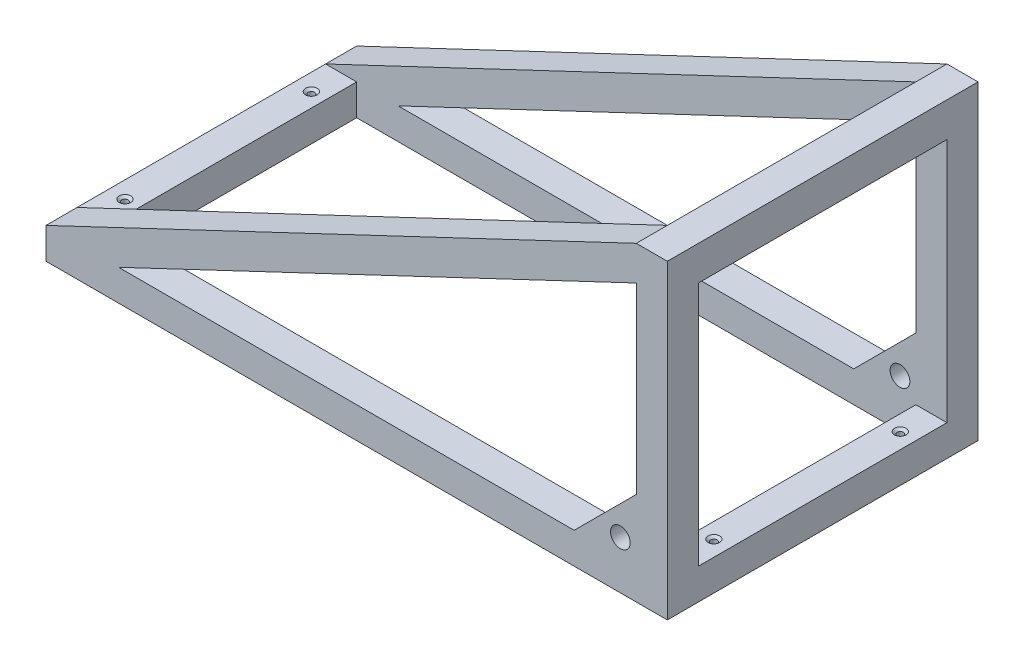
SolidWorks part; units mm, degrees
ref_plane "Front Plane" through (0, 0, 0) normal (0, 0, 1) x (1, 0, 0)
ref_plane "Top Plane" through (0, 0, 0) normal (0, 1, 0) x (1, 0, 0)
ref_plane "Right Plane" through (0, 0, 0) normal (1, 0, 0) x (0, 0, -1)
sketch "Sketch1" plane through (0, 0, 0) normal (0, 1, 0) x (1, 0, 0)
  line L0 (-90, 0) -> (90, 0) construction
  line L1 (90, 40) -> (-90, 40)
  line L2 (100, 27.3438) -> (100, 50)
  line L3 (100, 50) -> (-100, 50)
  line L4 (-100, 27.3438) -> (-100, 50)
  line L5 (0, 40) -> (0, -40) construction
  line L7 (86.3921, 17.3178) -> (86.3921, -17.3178) construction
  line L8 (-100, 27.3438) -> (-100, -27.3438)
  line L10 (-90, 40) -> (-90, -40)
  line L12 (100, 27.3438) -> (100, -27.3438)
  line L14 (90, 40) -> (90, -40)
  line L16 (-100, -27.3438) -> (-100, -50)
  line L17 (100, -50) -> (-100, -50)
  line L18 (100, -27.3438) -> (100, -50)
  line L19 (90, -40) -> (-90, -40)
  dimension "D1" = 200
  dimension "D2" = 100
  dimension "D3" = 10
  dimension "D4" = 10
  dimension "D5" = 10
extrude "Boss-Extrude1" add sketch "Sketch1" along normal blind 10
sketch "Sketch2" plane through (0, 10, 0) normal (0, 1, 0) x (1, 0, 0)
  line L0 (-100, -50) -> (100, -50) construction
  line L1 (90, -50) -> (100, -50)
  line L2 (90, -50) -> (90, -40)
  line L3 (90, -40) -> (100, -40)
  line L4 (100, -50) -> (100, -40)
  line L5 (100, -50) -> (100, 50) construction
  line L6 (-100, 0) -> (90.858, 0) construction
  line L7 (-100, 50) -> (-100, -50) construction
  line L8 (100, 50) -> (100, 40)
  line L9 (90, 40) -> (100, 40)
  line L10 (90, 50) -> (90, 40)
  line L11 (90, 50) -> (100, 50)
extrude "Boss-Extrude2" add sketch "Sketch2" along normal blind 90
sketch "Sketch3" plane through (0, 0, 50) normal (0, 0, 1) x (1, 0, 0)
  line L0 (-100, 10) -> (90, 100)
extrude "Extrude-Thin1" add sketch "Sketch3" against normal blind 10 thin
mirror "Mirror1" about plane through (0, 0, 0) normal (0, 0, 1) of "Extrude-Thin1"
sketch "Sketch4" plane through (0, 0, -40) normal (0, 0, 1) x (1, 0, 0)
  line L0 (90, 100) -> (90, 88.9348)
  line L1 (90, 88.9348) -> (100, 88.9348)
  line L2 (100, 100) -> (100, 0) construction
  line L3 (100, 88.9348) -> (100, 100)
  line L4 (100, 100) -> (90, 100)
extrude "Boss-Extrude3" add sketch "Sketch4" along normal up to surface (80 mm away) up to face at (27.1236, 35.8123, 40)
sketch "Sketch5" plane through (0, 0, 50) normal (0, 0, 1) x (1, 0, 0)
  line L0 (90, 30) -> (70, 10)
  line L1 (90, 88.9348) -> (90, 10) construction
  line L2 (-76.6402, 10) -> (90, 10) construction
  dimension "D1" = 20
  dimension "D2" = 20
rib "Rib3" sketch "Sketch5" sketch "Sketch5" thickness 10 extrusion direction parallel to sketch draft on no parameters "D1"=10
mirror "Mirror2" about plane through (0, 0, 0) normal (0, 0, 1) of "Rib3"
sketch "Sketch6" plane through (0, 0, 50) normal (0, 0, 1) x (1, 0, 0)
  circle A0 centre (84.883, 15.4833) radius 3.175
  dimension "D1" = 6.35
  dimension "D2" = 7.5
extrude "Cut-Extrude1" cut sketch "Sketch6" against normal up to surface (100 mm away)
hole_wizard "CSK for #1 Flat Head Machine Screw (100)1" positions "Sketch10" profile "Sketch9" countersink size "#1" standard "ANSI Inch"
sketch "Sketch10" plane through (0, 10, 0) normal (0, 1, 0) x (1, 0, 0)
  line L0 (-100, 40) -> (-90, 40) construction
  line L1 (-100, -40) -> (90, -40) construction
  point P0 (-94.5846, -30)
  point P2 (-94.5846, 30)
  point P4 (94.9781, 30)
  point P6 (94.9781, -30)
  point P9 (-95, 40)
  dimension "D1" = 10
  dimension "D2" = 10
sketch "Sketch9" plane through (-94.5846, 10, 30) normal (1, 0, 0) x (0, 0, 1)
  line L0 (0, 0) -> (0, 50.6181)
  line L1 (0, 50.6181) -> (1.0287, 50)
  line L2 (1.0287, 50) -> (1.0287, 0.6927)
  line L3 (1.0287, 0.6927) -> (1.8542, 0)
  line L5 (1.8542, 0) -> (0, 0)
  line L6 (-1.0287, 0.6927) -> (-1.8542, 0) construction
  line L10 (0, 50.6181) -> (-1.0287, 50) construction
  line L11 (0, -6.35) -> (0, 107.95) construction
  dimension "Hole Dia." = 2.0574
  dimension "Hole Depth" = 50
  dimension "Near C'Sink Dia." = 3.7084
  dimension "Near C'Sink Angle" = 100
  dimension "Drill Angle" = 118
